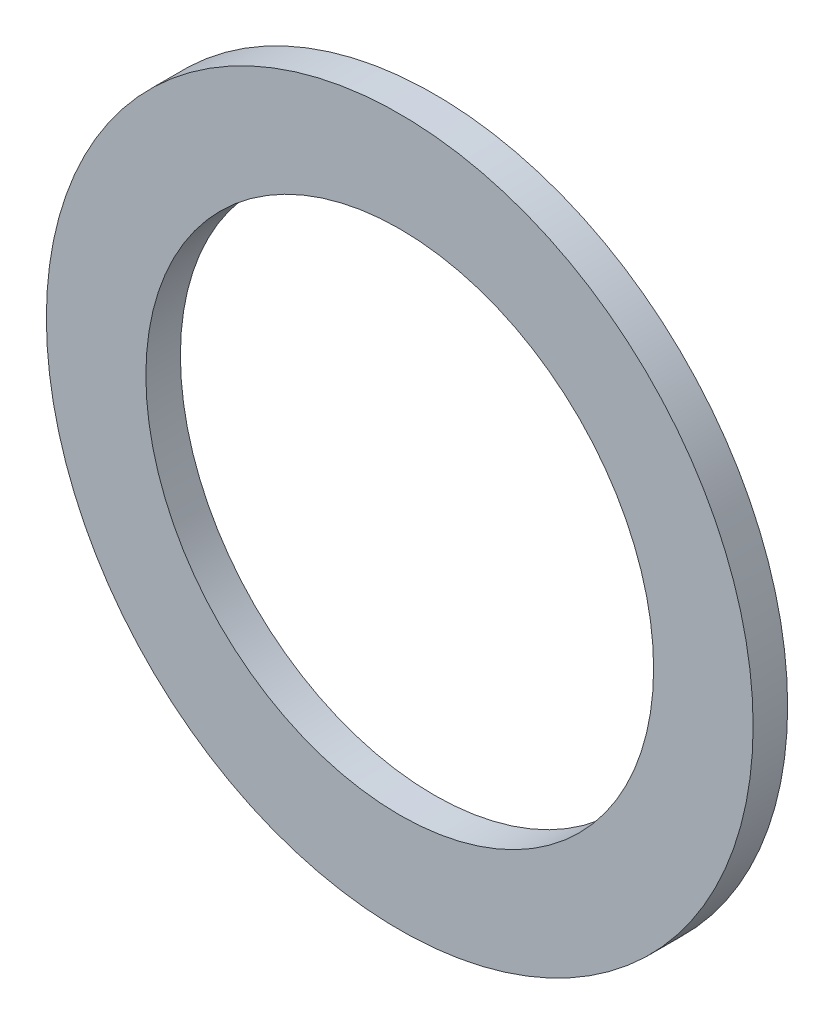
SolidWorks part; units mm, degrees
ref_plane "Plan1" through (0, 0, 0) normal (0, 0, 1) x (1, 0, 0)
ref_plane "Plan2" through (0, 0, 0) normal (0, 1, 0) x (1, 0, 0)
ref_plane "Plan3" through (0, 0, 0) normal (1, 0, 0) x (0, 0, -1)
sketch "Esquisse1" plane through (0, 0, 0) normal (0, 0, 1) x (1, 0, 0)
  circle A0 centre (0, 0) radius 12.5
  circle A1 centre (0, 0) radius 12.5 construction
  circle A2 centre (0, 0) radius 17.4
  dimension "D1" = 34.8
extrude "Base-Extrusion" add sketch "Esquisse1" along normal blind 1.7
